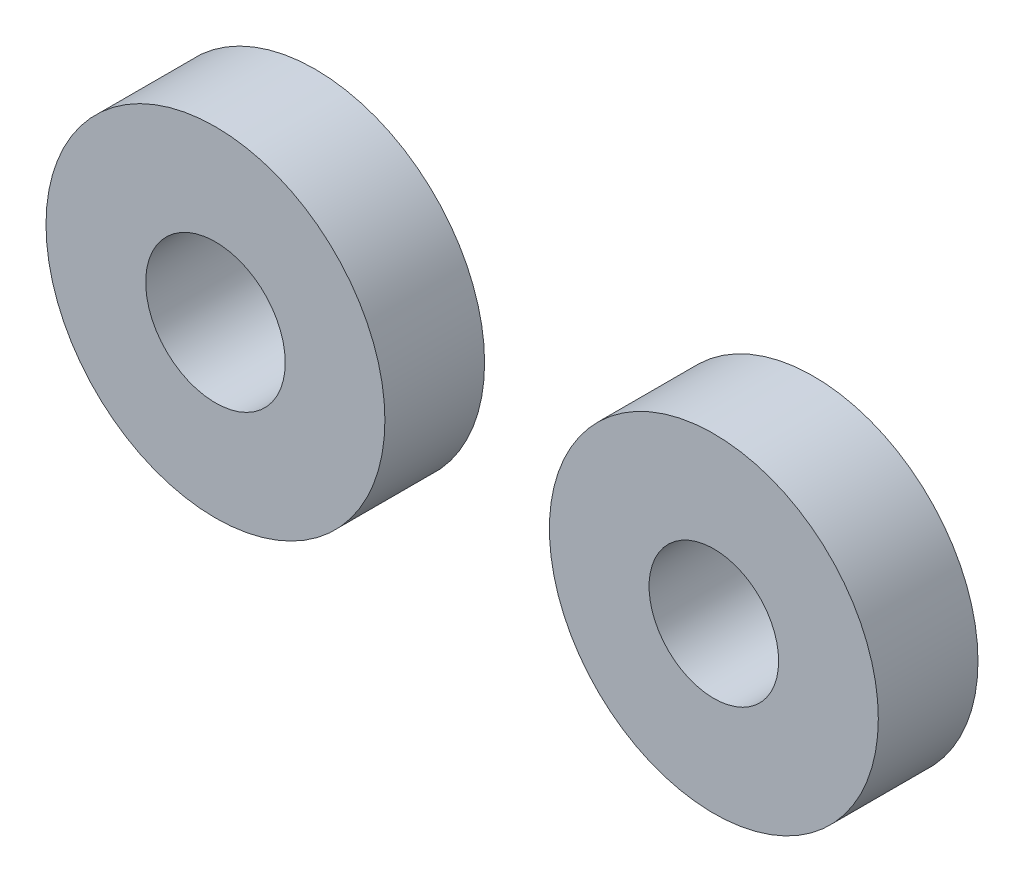
SolidWorks part; units mm, degrees
ref_plane "Front Plane" through (0, 0, 0) normal (0, 0, 1) x (1, 0, 0)
ref_plane "Top Plane" through (0, 0, 0) normal (0, 1, 0) x (1, 0, 0)
ref_plane "Right Plane" through (0, 0, 0) normal (1, 0, 0) x (0, 0, -1)
sketch "Sketch1" plane through (0, 0, 0) normal (0, 0, 1) x (1, 0, 0)
  circle A0 centre (0, 0) radius 1.778
  circle A2 centre (0, 0) radius 4.318
  circle A3 centre (12.7, -0.2988) radius 1.651
  circle A4 centre (12.7, -0.2988) radius 4.191
  dimension "D2" = 3.556
  dimension "D3" = 3.302
  dimension "D4" = 2.54
  dimension "D5" = 2.54
  dimension "D1" = 12.7
extrude "Boss-Extrude1" add sketch "Sketch1" along normal blind 2.54
